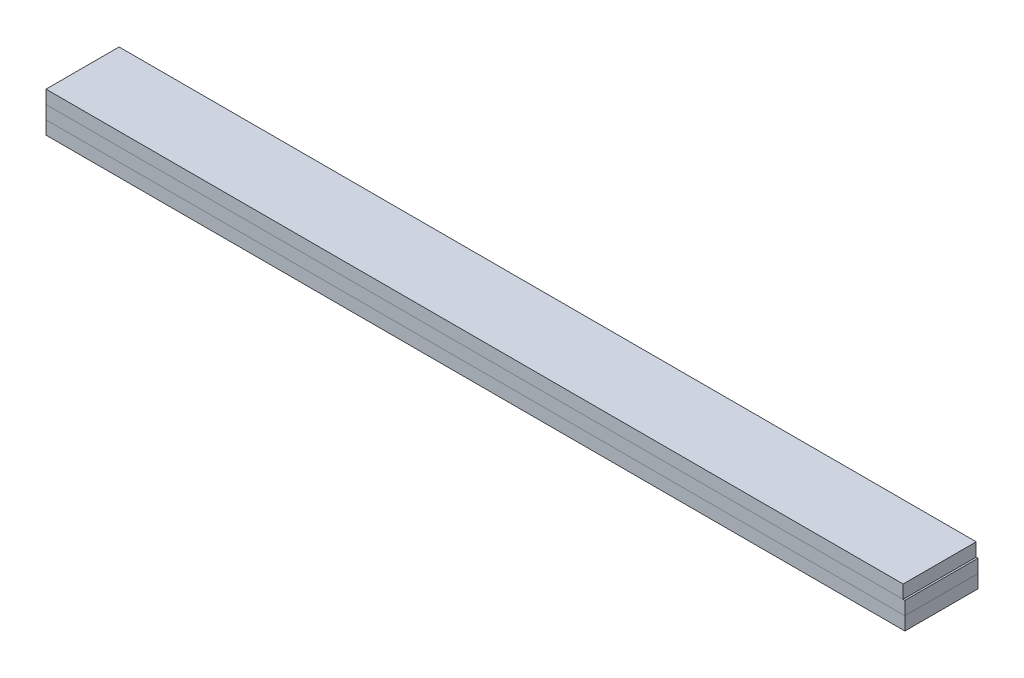
SolidWorks part; units mm, degrees
ref_plane "Front Plane" through (0, 0, 0) normal (0, 0, 1) x (1, 0, 0)
ref_plane "Top Plane" through (0, 0, 0) normal (0, 1, 0) x (1, 0, 0)
ref_plane "Right Plane" through (0, 0, 0) normal (1, 0, 0) x (0, 0, -1)
sketch "Sketch2" plane through (0, 0, 0) normal (0, 1, 0) x (1, 0, 0)
  line L0 (-35.367, 3.1088) -> (-35.367, -2.3912)
  line L1 (-35.367, -2.3912) -> (34.333, -2.3912)
  line L2 (34.333, -2.3912) -> (34.333, 3.1088)
  line L3 (34.333, 3.1088) -> (-35.367, 3.1088)
extrude "Boss-Extrude1" add sketch "Sketch2" along normal blind 1
sketch "Sketch4" plane through (0, 1, 0) normal (0, 1, 0) x (1, 0, 0)
  line L4 (34.333, 3.1088) -> (-35.367, 3.1088)
  line L5 (-35.367, 3.1088) -> (-35.367, -2.3912)
  line L6 (-35.367, -2.3912) -> (34.333, -2.3912)
  line L7 (34.333, -2.3912) -> (34.333, 3.1088)
  line L8 (34.333, 3.1088) -> (-35.367, 3.1088)
  line L9 (-35.367, 3.1088) -> (-35.367, -2.3912)
  line L10 (-35.367, -2.3912) -> (34.333, -2.3912)
  line L11 (34.333, -2.3912) -> (34.333, 3.1088)
  dimension "D1" = 0
extrude "Boss-Extrude2" add sketch "Sketch4" along normal blind 1 separate body
sketch "Sketch5" plane through (0, 2, 0) normal (0, 1, 0) x (1, 0, 0)
  line L1 (34.15, 3.1088) -> (34.15, -2.3912)
  line L4 (34.333, -2.3912) -> (34.333, 3.1088)
  line L5 (34.333, 3.1088) -> (-35.367, 3.1088)
  line L6 (-35.367, 3.1088) -> (-35.367, -2.3912)
  line L7 (-35.367, -2.3912) -> (34.333, -2.3912)
  line L9 (34.15, 3.1088) -> (-35.367, 3.1088)
  line L10 (-35.367, 3.1088) -> (-35.367, -2.3912)
  line L11 (-35.367, -2.3912) -> (34.15, -2.3912)
  dimension "D1" = 0
extrude "Boss-Extrude3" add sketch "Sketch5" along normal blind 1 separate body
sketch "Sketch7" plane through (0, 3, 0) normal (0, 1, 0) x (1, 0, 0)
  line L6 (29.133, -2.3912) -> (29.133, 3.1088)
  line L7 (34.15, 3.1088) -> (-35.367, 3.1088) construction
  line L8 (29.133, 3.1088) -> (34.333, 3.1088)
  line L9 (34.333, 3.1088) -> (34.333, -2.3912)
  line L10 (34.333, -2.3912) -> (34.333, 3.1088) construction
  line L11 (34.333, -2.3912) -> (29.133, -2.3912)
extrude "Cut-Extrude3" cut sketch "Sketch7" against normal blind 1
sketch "Sketch8" plane through (0, 2, 0) normal (0, 1, 0) x (1, 0, 0)
  line L0 (29.2668, -2.3912) -> (29.2668, 3.1088)
  line L1 (-35.367, -2.3912) -> (34.333, -2.3912) construction
  line L2 (34.333, 3.1088) -> (-35.367, 3.1088) construction
  line L3 (29.2668, -2.3912) -> (34.333, -2.3912)
  line L4 (34.333, -2.3912) -> (34.333, 3.1088)
  line L5 (34.333, 3.1088) -> (29.2668, 3.1088)
extrude "Cut-Extrude4" cut sketch "Sketch8" against normal blind 20
